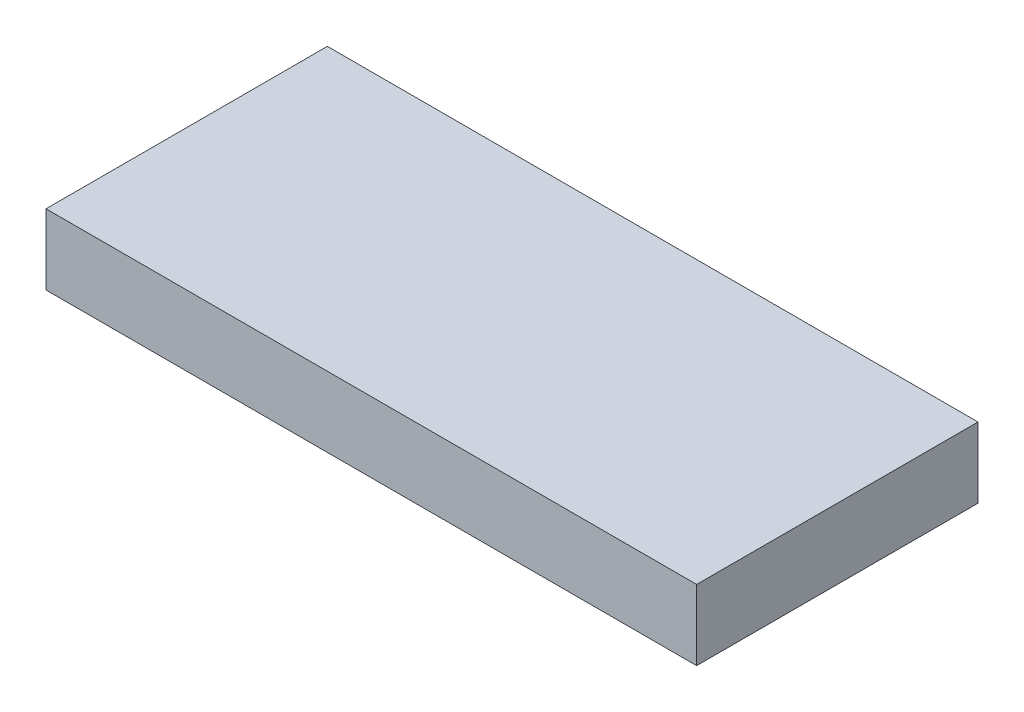
SolidWorks part; units mm, degrees
material "Beech"
ref_plane "Front Plane" through (0, 0, 0) normal (0, 0, 1) x (1, 0, 0)
ref_plane "Top Plane" through (0, 0, 0) normal (0, 1, 0) x (1, 0, 0)
ref_plane "Right Plane" through (0, 0, 0) normal (1, 0, 0) x (0, 0, -1)
sketch "Sketch1" plane through (0, 0, 0) normal (0, 1, 0) x (1, 0, 0)
  line L1 (0, 0) -> (304.8, 0)
  line L2 (0, 0) -> (0, 304.8)
  line L3 (0, 304.8) -> (304.8, 304.8)
  line L4 (304.8, 0) -> (304.8, 304.8)
  dimension "D1" = 304.8
  dimension "D2" = 304.8
extrude "Boss-Extrude1" add sketch "Sketch1" along normal blind 6.35
sketch "Sketch2" plane through (0, 6.35, 0) normal (0, 1, 0) x (1, 0, 0)
  line L1 (304.8, 304.8) -> (0, 304.8) construction
  line L2 (58.7375, 304.8) -> (58.7375, 279.4)
  line L3 (58.7375, 279.4) -> (0, 279.4)
  line L4 (0, 304.8) -> (0, 0) construction
  line L6 (0, 279.4) -> (0, 0)
  line L7 (0, 0) -> (304.8, 0)
  line L8 (304.8, 0) -> (304.8, 304.8)
  line L9 (304.8, 304.8) -> (58.7375, 304.8)
  dimension "D1" = 58.7375
  dimension "D2" = 25.4
extrude "Cut-Extrude2" cut sketch "Sketch2" against normal blind 6.35 contours L3 L6 L7 L8 L9 L2
